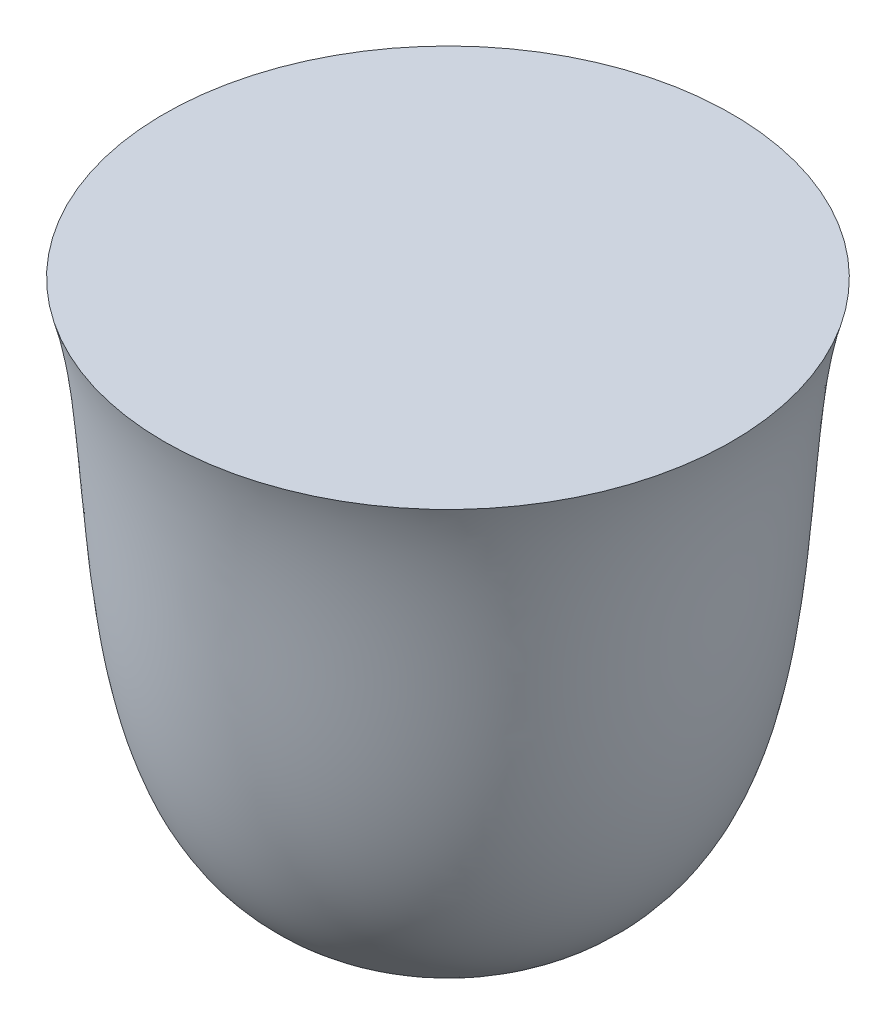
SolidWorks part; units mm, degrees
ref_plane "Front" through (0, 0, 0) normal (0, 0, 1) x (1, 0, 0)
ref_plane "Top" through (0, 0, 0) normal (0, 1, 0) x (1, 0, 0)
ref_plane "Right" through (0, 0, 0) normal (1, 0, 0) x (0, 0, -1)
sketch "Sketch1" plane through (0, 0, 0) normal (0, 0, 1) x (1, 0, 0)
  line L0 (0, 0) -> (0, -150) construction
  line L3 (7.3631, -146) -> (7.3631, -145.8631)
  line L5 (0, 0) -> (75, 0)
  line L6 (3.3631, -150) -> (0, -150)
  line L7 (0, 0) -> (0, -150)
  arc A0 (3.3631, -150) -> (7.3631, -146) centre (3.3631, -146) ccw
  arc A1 (7.3631, -145.8631) -> (11.1269, -141.8701) centre (11.3631, -145.8631) cw
  spline S0 degree 3 poles (11.1269, -141.8701) (26.0388, -140.9878) (76.3506, -116.5802) (64.4107, -34.5071) (75, 0) knots 0.017668 0.017668 0.017668 0.017668 0.232438 1 1 1 1
  point P4 (37.6843, -116.5817)
  point P5 (78.1951, -69.5206)
  point P6 (40.4318, -121.8012)
  point P9 (67.4395, -59.616)
  point P10 (45.0628, -127.5587)
  point P20 (-7.3631, -150)
  dimension "D4" = 4
  dimension "D2" = 4
  dimension "D1" = 150
revolve "Revolve5" add sketch "Sketch1" angle 360 about L0
